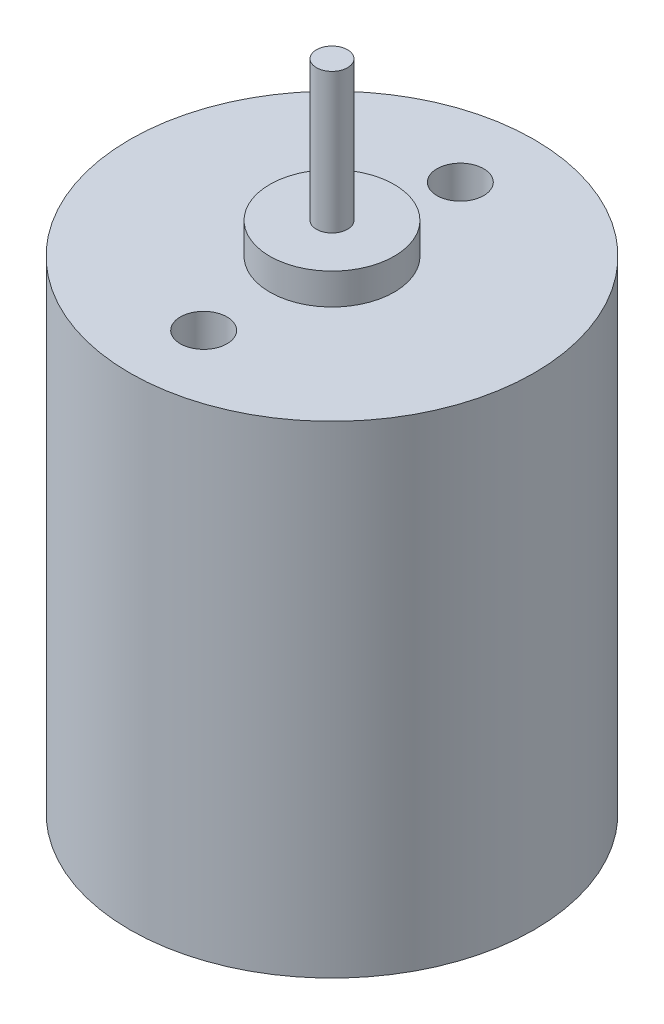
SolidWorks part; units mm, degrees
ref_plane "Front Plane" through (0, 0, 0) normal (0, 0, 1) x (1, 0, 0)
ref_plane "Top Plane" through (0, 0, 0) normal (0, 1, 0) x (1, 0, 0)
ref_plane "Right Plane" through (0, 0, 0) normal (1, 0, 0) x (0, 0, -1)
sketch "Sketch1" plane through (0, 0, 0) normal (0, 1, 0) x (1, 0, 0)
  circle A0 centre (0, 0) radius 13
  dimension "D1" = 26
extrude "Boss-Extrude1" add sketch "Sketch1" along normal blind 31
sketch "Sketch2" plane through (0, 31, 0) normal (0, 1, 0) x (1, 0, 0)
  circle A0 centre (0, 0) radius 4
  dimension "D1" = 8
extrude "Boss-Extrude2" add sketch "Sketch2" along normal blind 2
sketch "Sketch3" plane through (0, 33, 0) normal (0, 1, 0) x (1, 0, 0)
  circle A0 centre (0, 0) radius 1
  dimension "D1" = 2
extrude "Boss-Extrude3" add sketch "Sketch3" along normal blind 9
sketch "Sketch4" plane through (0, 31, 0) normal (0, 1, 0) x (1, 0, 0)
  circle A0 centre (0, -8.25) radius 1.5
  circle A1 centre (0, 8.25) radius 1.5
  dimension "D1" = 3
  dimension "D2" = 8.25
  dimension "D3" = 8.25
extrude "Cut-Extrude1" cut sketch "Sketch4" against normal blind 5
